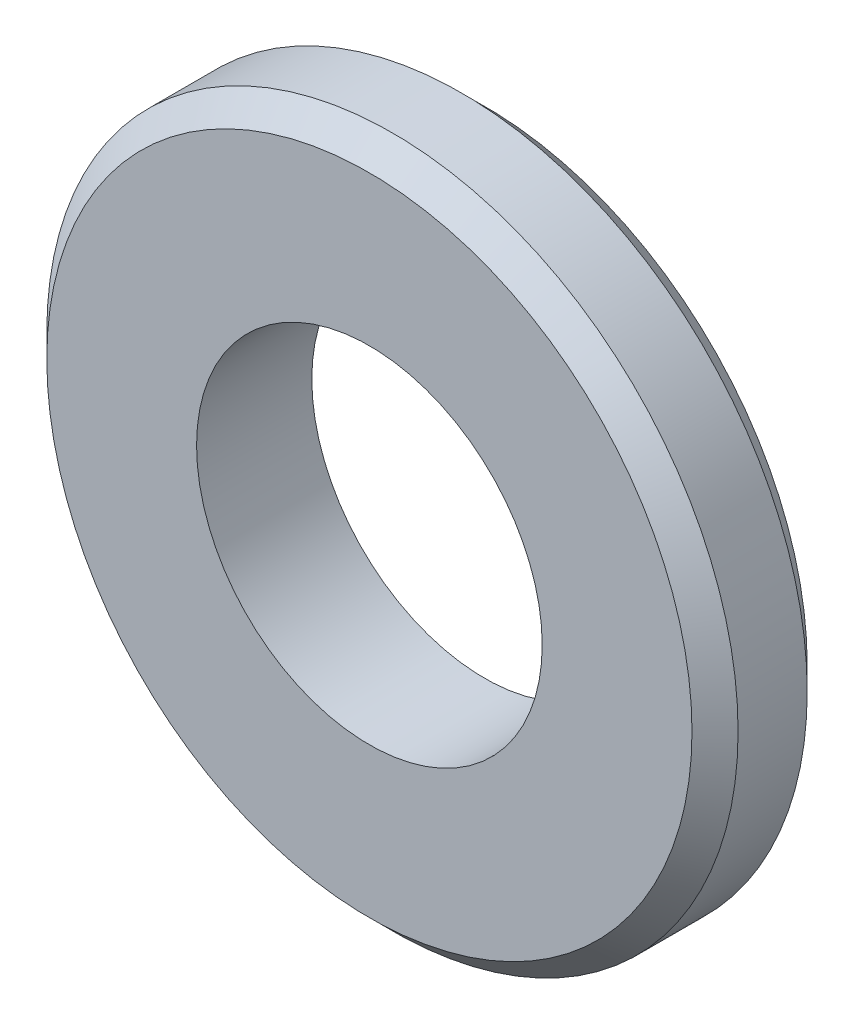
SolidWorks part; units mm, degrees
ref_plane "前视基准面" through (0, 0, 0) normal (0, 0, 1) x (1, 0, 0)
ref_plane "上视基准面" through (0, 0, 0) normal (0, 1, 0) x (1, 0, 0)
ref_plane "右视基准面" through (0, 0, 0) normal (1, 0, 0) x (0, 0, -1)
sketch "草图1" plane through (0, 0, 0) normal (0, 0, 1) x (1, 0, 0)
  circle A0 centre (0, 0) radius 1.5
  circle A1 centre (0, 0) radius 3
  dimension "D1" = 3
  dimension "D2" = 6
extrude "凸台-拉伸1" add sketch "草图1" along normal mid plane 1
chamfer "倒角1" distance 0.2 angle 45 2 edges at (3, 0, 0.5) (3, 0, -0.5)
